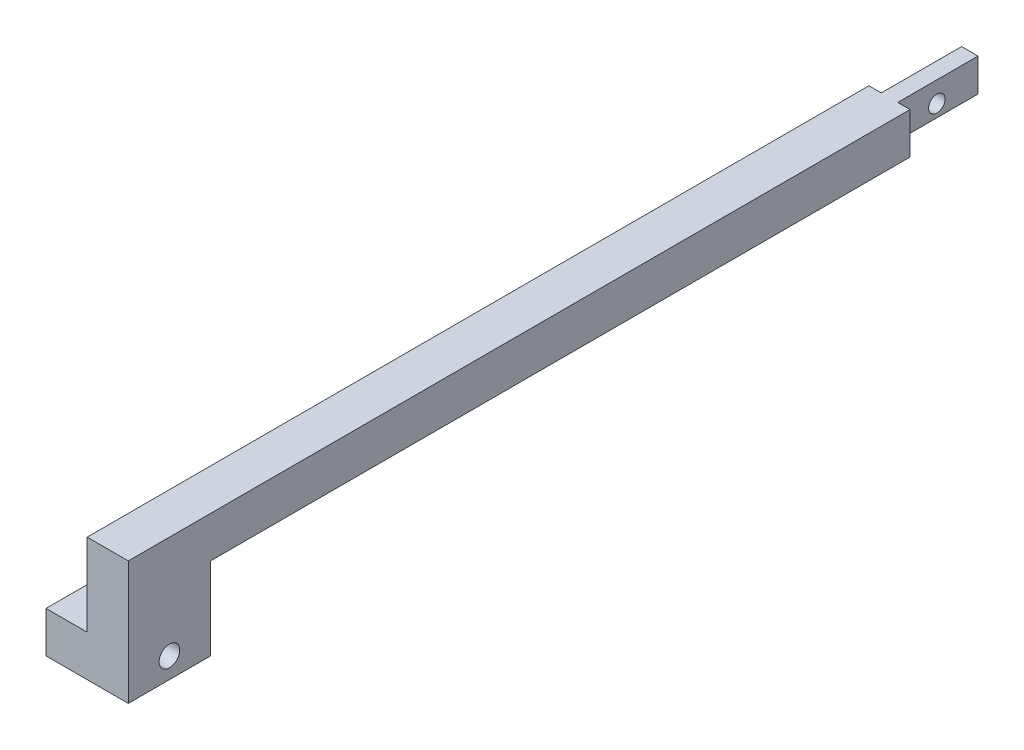
SolidWorks part; units mm, degrees
ref_plane "Front Plane" through (0, 0, 0) normal (0, 0, 1) x (1, 0, 0)
ref_plane "Top Plane" through (0, 0, 0) normal (0, 1, 0) x (1, 0, 0)
ref_plane "Right Plane" through (0, 0, 0) normal (1, 0, 0) x (0, 0, -1)
sketch "Sketch2" plane through (0, 0, 0) normal (0, 0, 1) x (1, 0, 0)
  line L0 (0, 0) -> (0, 10)
  line L1 (0, 10) -> (10, 10)
  line L2 (10, 10) -> (10, 30)
  line L3 (10, 30) -> (20, 30)
  line L4 (20, 30) -> (20, 0)
  line L5 (20, 0) -> (0, 0)
  dimension "D1" = 10
  dimension "D2" = 10
  dimension "D3" = 30
  dimension "D4" = 20
extrude "Boss-Extrude1" add sketch "Sketch2" along normal blind 190
sketch "Sketch3" plane through (20, 0, 0) normal (1, 0, 0) x (0, 0, -1)
  line L1 (-170, 20) -> (0, 20)
  line L2 (-170, 20) -> (-170, 0)
  line L3 (-170, 0) -> (0, 0)
  line L4 (0, 20) -> (0, 0)
  dimension "D1" = 20
  dimension "D2" = 170
extrude "Cut-Extrude1" cut sketch "Sketch3" against normal blind 190
sketch "Sketch4" plane through (0, 0, 0) normal (0, 0, -1) x (-1, 0, 0)
  line L0 (-20, 30) -> (-10, 30) construction
  line L1 (-17, 30) -> (-13, 30)
  line L2 (-17, 30) -> (-17, 25)
  line L3 (-17, 25) -> (-13, 25)
  line L4 (-13, 30) -> (-13, 25)
  line L5 (-20, 20) -> (-20, 30) construction
  line L6 (-10, 30) -> (-10, 20) construction
  dimension "D1" = 5
  dimension "D2" = 3
  dimension "D3" = 3
extrude "Boss-Extrude2" add sketch "Sketch4" along normal blind 19.5
sketch "Sketch5" plane through (0, 0, 0) normal (-1, 0, 0) x (0, 0, 1)
  line L0 (190, 10) -> (190, 0) construction
  line L1 (190, 10) -> (170, 10) construction
  circle A0 centre (180, 5) radius 2.75
  dimension "D1" = 5.5
  dimension "D2" = 10
  dimension "D3" = 5
extrude "Cut-Extrude3" cut sketch "Sketch5" against normal blind 10
ref_plane "Plane1" through (17, 25, -19.5) normal (0, 0, 1) x (1, 0, 0)
sketch "Sketch7" plane through (0, 25, 0) normal (0, -1, 0) x (1, 0, 0)
  line L0 (22.3625, -19.5) -> (11.6375, -19.5) construction
  line L1 (13, 0) -> (17, 0)
  line L2 (13, 0) -> (13, -19.5)
  line L3 (13, -19.5) -> (17, -19.5)
  line L4 (17, 0) -> (17, -19.5)
  line L5 (17, -19.5) -> (17, 0) construction
extrude "Boss-Extrude3" add sketch "Sketch7" along normal blind 3
sketch "Sketch8" plane through (0, 0, 0) normal (-1, 0, 0) x (0, 0, 1)
  circle A0 centre (180, 5) radius 2.75
  circle A1 centre (180, 5) radius 2.5
  dimension "D1" = 5
extrude "Boss-Extrude4" add sketch "Sketch8" against normal through all
sketch "Sketch9" plane through (0, 0, 0) normal (-1, 0, 0) x (0, 0, 1)
  circle A0 centre (180, 5) radius 2.5
extrude "Cut-Extrude4" cut sketch "Sketch9" against normal through all
sketch "Sketch10" plane through (13, 0, 0) normal (-1, 0, 0) x (0, 0, 1)
  line L0 (-19.5, 30) -> (0, 30) construction
  line L1 (-19.5, -30) -> (-19.5, 80) construction
  circle A0 centre (-9.5, 25) radius 2
  dimension "D1" = 4
  dimension "D2" = 5
  dimension "D3" = 10
extrude "Cut-Extrude5" cut sketch "Sketch10" against normal through all
